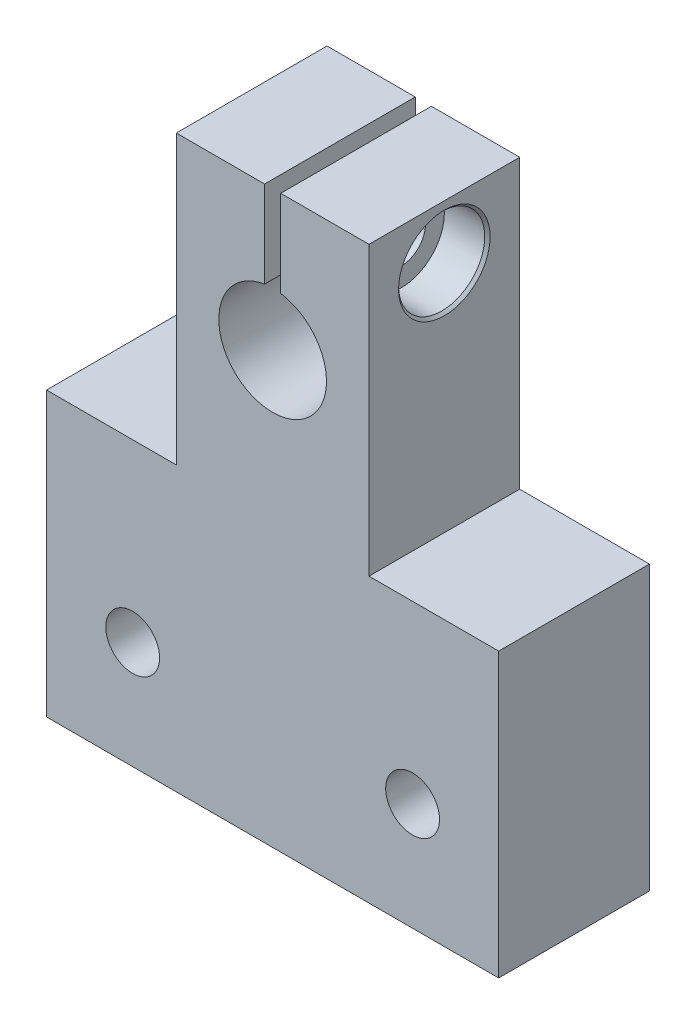
SolidWorks part; units mm, degrees
ref_plane "Front Plane" through (0, 0, 0) normal (0, 0, 1) x (1, 0, 0)
ref_plane "Top Plane" through (0, 0, 0) normal (0, 1, 0) x (1, 0, 0)
ref_plane "Right Plane" through (0, 0, 0) normal (1, 0, 0) x (0, 0, -1)
sketch "Sketch1" plane through (0, 0, 0) normal (0, 0, 1) x (1, 0, 0)
  line L0 (0, 0) -> (0, 33) construction
  line L1 (-21, 6.3) -> (-8.95, 6.3)
  line L2 (-21, 6.3) -> (-21, 0)
  line L3 (-21, 0) -> (21, 0)
  line L4 (21, 6.3) -> (21, 0)
  line L9 (-8.95, 33) -> (-0.75, 33)
  line L10 (-8.95, 33) -> (-8.95, 6.3)
  line L12 (8.95, 33) -> (8.95, 6.3)
  line L13 (-0.75, 33) -> (-0.75, 24.9434)
  line L14 (0.75, 33) -> (0.75, 24.9434)
  line L15 (0.75, 33) -> (8.95, 33)
  line L16 (8.95, 6.3) -> (21, 6.3)
  arc A0 (-0.75, 24.9434) -> (0.75, 24.9434) centre (0, 20) ccw
  dimension "D5" = 10
  dimension "D6" = 20
  dimension "D1" = 42
  dimension "D2" = 6.3
  dimension "D3" = 26.7
  dimension "D4" = 17.9
  dimension "D7" = 1.5
extrude "Boss-Extrude1" add sketch "Sketch1" along normal mid plane 14
sketch "Sketch2" plane through (0, 6.3, 0) normal (0, 1, 0) x (1, 0, 0)
  line L0 (-16, 0) -> (16, 0) construction
  circle A0 centre (16, 0) radius 2.6
  circle A1 centre (-16, 0) radius 2.6
  point P4 (0, 0)
  dimension "D1" = 5.2
  dimension "D3" = 32
extrude "Cut-Extrude1" [suppressed] cut sketch "Sketch2" against normal up to next
chamfer "Chamfer1" [suppressed] distance 0.5 angle 45
hole_wizard "CBORE for M4 SHCS2" positions "Sketch3" profile "Sketch4" counterbore size "M4" standard "ANSI Metric" end condition up to next
sketch "Sketch3" plane through (8.95, 0, 0) normal (1, 0, 0) x (0, 0, -1)
  line L0 (0, 33) -> (0, 28) construction
  line L1 (-7, 33) -> (7, 33) construction
  point P2 (0, 28)
  dimension "D1" = 5
sketch "Sketch4" plane through (8.95, 28, 0) normal (0, 1, 0) x (0, 0, -1)
  line L0 (0, 0) -> (0, 8.2)
  line L1 (0, 8.2) -> (2.25, 8.2)
  line L3 (2.25, 8.2) -> (2.25, 4)
  line L4 (4, 4) -> (2.25, 4)
  line L5 (4, 4) -> (4, 0.25)
  line L6 (4, 0.25) -> (4.25, 0)
  line L7 (4.25, 0) -> (0, 0)
  line L8 (-4, 0.25) -> (-4.25, 0) construction
  line L11 (0, -6.35) -> (0, 107.95) construction
  dimension "Thru Hole Dia." = 4.5
  dimension "Thru Hole Depth" = 8.2
  dimension "C'Bore Dia." = 8
  dimension "C'Bore Depth" = 4
  dimension "Near C'Sink Dia." = 8.5
  dimension "Near C'Sink Angle" = 90
hole_wizard "M4x0.7 Tapped Hole1" positions "Sketch5" profile "Sketch6" tap size "M4x0.7" standard "ANSI Metric" end condition up to next
sketch "Sketch5" plane through (-0.75, 0, 0) normal (1, 0, 0) x (0, 0, -1)
  point P0 (0, 28)
sketch "Sketch6" plane through (-0.75, 28, 0) normal (0, 1, 0) x (0, 0, -1)
  line L0 (0, 0) -> (0, 8.2)
  line L1 (0, 8.2) -> (1.65, 8.2)
  line L2 (1.65, 8.2) -> (1.65, 0)
  line L5 (1.65, 0) -> (0, 0)
  line L11 (0, -6.35) -> (0, 107.95) construction
  dimension "Thru Tap Drill Dia." = 3.3
  dimension "Thru Tap Drill Depth" = 8.2
cosmetic thread "Hole Thread1" parameters "D2"=4
sketch "Sketch7" plane through (0, 0, 0) normal (0, -1, 0) x (1, 0, 0)
  line L4 (-21, -7) -> (21, -7)
  line L5 (21, -7) -> (21, 7)
  line L6 (21, 7) -> (-21, 7)
  line L7 (-21, 7) -> (-21, -7)
  line L8 (-21, -7) -> (21, -7)
  line L9 (21, -7) -> (21, 7)
  line L10 (21, 7) -> (-21, 7)
  line L11 (-21, 7) -> (-21, -7)
  dimension "D1" = 0
extrude "Boss-Extrude2" add sketch "Sketch7" along normal blind 20
sketch "Sketch8" plane through (0, 0, 7) normal (0, 0, 1) x (1, 0, 0)
  line L0 (-21, -10) -> (21, -10) construction
  line L1 (-21, 6.3) -> (-21, -20) construction
  line L2 (21, -20) -> (21, 6.3) construction
  line L3 (21, -20) -> (-21, -20) construction
  circle A0 centre (-13, -10) radius 2.5
  circle A1 centre (13, -10) radius 2.5
  dimension "D2" = 8
  dimension "D3" = 8
  dimension "D4" = 5
  dimension "D1" = 10
extrude "Cut-Extrude2" cut sketch "Sketch8" against normal blind 28
